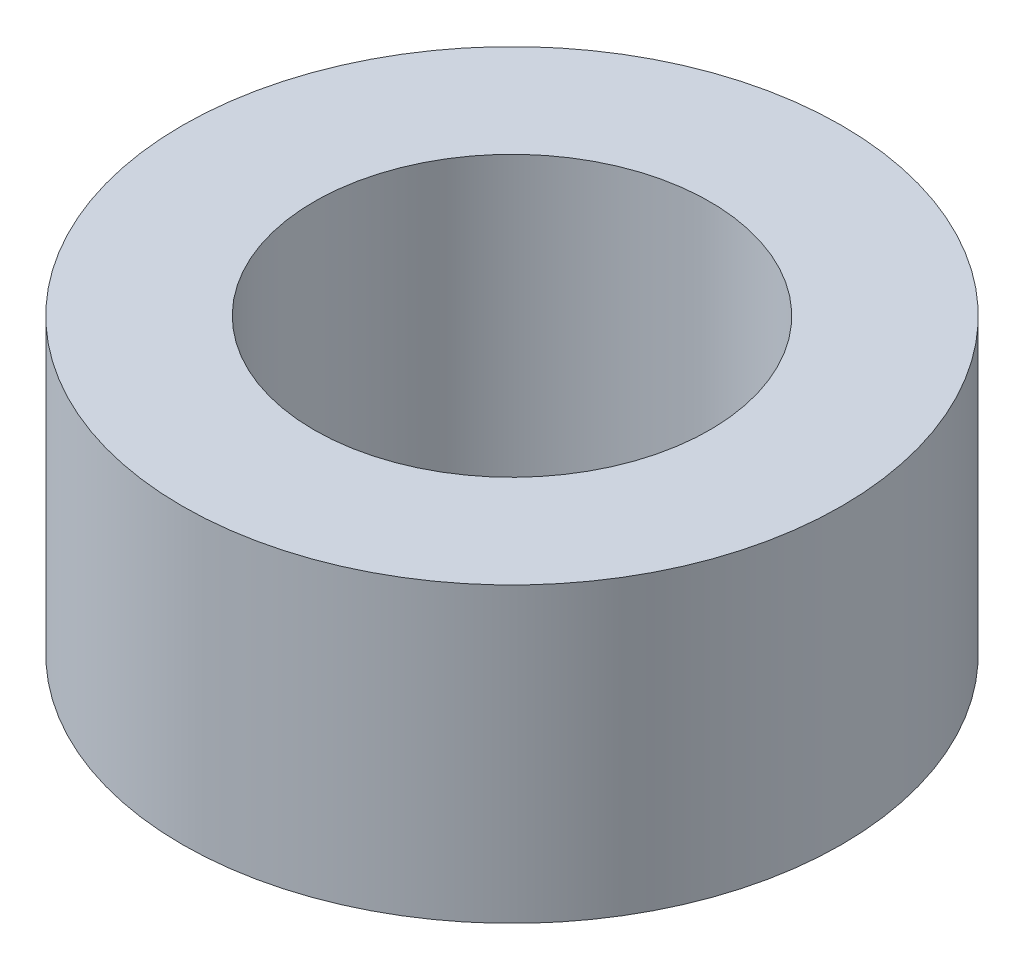
SolidWorks part; units mm, degrees
ref_plane "Front Plane" through (0, 0, 0) normal (0, 0, 1) x (1, 0, 0)
ref_plane "Top Plane" through (0, 0, 0) normal (0, 1, 0) x (1, 0, 0)
ref_plane "Right Plane" through (0, 0, 0) normal (1, 0, 0) x (0, 0, -1)
sketch "Sketch1" plane through (0, 0, 0) normal (0, 1, 0) x (1, 0, 0)
  circle A0 centre (0, 0) radius 2.25
  circle A1 centre (0, 0) radius 1.35
  dimension "D1" = 4.5
  dimension "D2" = 2.7
extrude "Boss-Extrude1" add sketch "Sketch1" along normal blind 2
